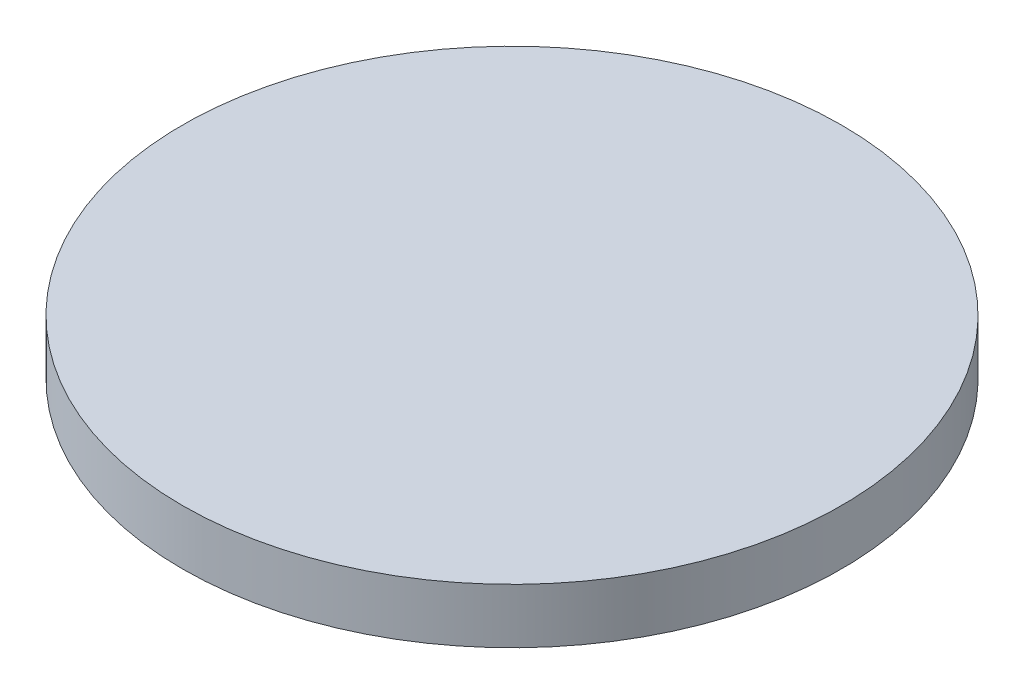
SolidWorks part; units mm, degrees
ref_plane "Front Plane" through (0, 0, 0) normal (0, 0, 1) x (1, 0, 0)
ref_plane "Top Plane" through (0, 0, 0) normal (0, 1, 0) x (1, 0, 0)
ref_plane "Right Plane" through (0, 0, 0) normal (1, 0, 0) x (0, 0, -1)
sketch "Sketch1" plane through (0, 0, 0) normal (0, 1, 0) x (1, 0, 0)
  circle A0 centre (0, 0) radius 30
  dimension "D1" = 60
extrude "Boss-Extrude1" add sketch "Sketch1" along normal mid plane 5
